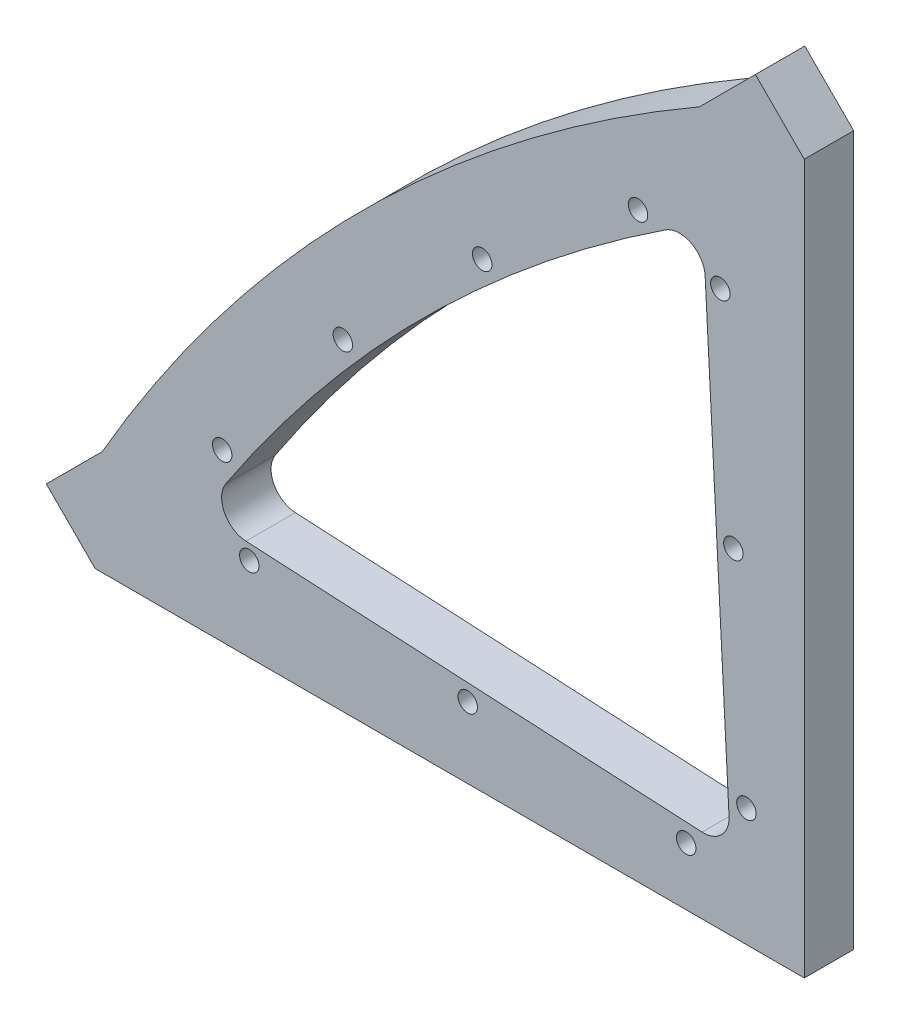
SolidWorks part; units mm, degrees
ref_plane "Front Plane" through (0, 0, 0) normal (0, 0, 1) x (1, 0, 0)
ref_plane "Top Plane" through (0, 0, 0) normal (0, 1, 0) x (1, 0, 0)
ref_plane "Right Plane" through (0, 0, 0) normal (1, 0, 0) x (0, 0, -1)
sketch "Sketch1" plane through (0, 0, 0) normal (0, 0, 1) x (1, 0, 0)
  line L2 (-60.2624, -86.0896) -> (122.0368, -86.0896)
  line L6 (-42.1742, -86.4706) -> (122.4178, -86.4706) construction
  line L7 (117.3378, -81.3906) -> (130.0378, -94.0906) construction
  line L8 (122.0368, 96.2096) -> (122.0368, -86.0896)
  line L9 (-72.8348, -73.5173) -> (-60.2624, -86.0896)
  line L10 (122.0368, -86.0896) -> (-41.4122, 77.3594) construction
  line L15 (-194.9829, 48.6309) -> (-70.337, -76.0151) construction
  line L31 (-71.7047, -74.6473) -> (-63.733, -82.6191) construction
  line L32 (-58.4664, -59.1489) -> (-72.8348, -73.5173)
  line L33 (95.096, 94.4135) -> (109.4644, 108.7819)
  line L34 (109.4644, 108.7819) -> (122.0368, 96.2096)
  arc A2 (95.096, 94.4135) -> (-58.4664, -59.1489) centre (304.2547, -268.3076) ccw
  arc A3 (86.8507, 75.0529) -> (-39.1057, -50.9035) centre (304.2547, -268.3076) ccw construction
  dimension "D1" = 17.78
  dimension "D2" = 0.381
  dimension "D3" = 20.32
extrude "Boss-Extrude1" add sketch "Sketch1" along normal blind 12.7
sketch "Sketch2" plane through (0, 0, 12.7) normal (0, 0, 1) x (1, 0, 0)
  line L0 (106.3271, 64.9875) -> (112.928, -60.9641) construction
  line L1 (96.9113, -76.9808) -> (-29.0404, -70.38) construction
  line L2 (96.5484, 57.4472) -> (102.6933, -59.8056)
  line L4 (95.7527, -66.7462) -> (-21.5001, -60.6012)
  line L5 (96.1811, 64.4558) -> (102.7819, -61.4958) construction
  line L6 (97.443, -66.8347) -> (-28.5086, -60.2339) construction
  arc A0 (112.928, -60.9641) -> (96.9113, -76.9808) centre (97.7089, -61.7617) cw construction
  arc A1 (96.9113, -76.9808) -> (112.928, -60.9641) centre (97.7089, -61.7617) ccw construction
  arc A2 (-29.0404, -70.38) -> (-39.1057, -50.9035) centre (-28.3757, -57.6974) cw construction
  arc A3 (-39.1057, -50.9035) -> (86.8507, 75.0529) centre (304.2547, -268.3076) cw construction
  arc A4 (86.8507, 75.0529) -> (106.3271, 64.9875) centre (93.6445, 64.3229) cw construction
  arc A5 (-26.6699, -50.374) -> (86.3212, 62.617) centre (304.2547, -268.3076) cw
  arc A12 (-30.5217, -56.3386) -> (92.2858, 66.4689) centre (304.2547, -268.3076) cw construction
  arc A13 (86.3212, 62.617) -> (96.5484, 57.4472) centre (89.9534, 57.1016) cw
  arc A24 (-21.5001, -60.6012) -> (-26.6699, -50.374) centre (-21.1544, -54.0062) cw
  arc A25 (95.7527, -66.7462) -> (102.6933, -59.8056) centre (96.0984, -60.1512) ccw
  arc A35 (92.2858, 66.4689) -> (96.1811, 64.4558) centre (93.6445, 64.3229) cw construction
  arc A36 (-28.5086, -60.2339) -> (-30.5217, -56.3386) centre (-28.3757, -57.6974) cw construction
  arc A37 (102.7819, -61.4958) -> (97.443, -66.8347) centre (97.7089, -61.7617) cw construction
  dimension "D2" = 6.604
  dimension "D1" = 10.16
extrude "Cut-Extrude1" cut sketch "Sketch2" against normal through all
sketch "Sketch3" plane through (0, 0, 0) normal (0, 0, -1) x (-1, 0, 0)
  circle A0 centre (-100.4496, 56.5997) radius 2.5
  circle A1 centre (-79.2876, 63.5687) radius 2.5
  circle A2 centre (-39.2281, 32.5461) radius 2.5
  circle A3 centre (-3.401, -3.281) radius 2.5
  circle A4 centre (27.6215, -43.3404) radius 2.5
  circle A5 centre (20.6525, -64.5024) radius 2.5
  circle A6 centre (-35.5084, -67.8561) radius 2.5
  circle A7 centre (-91.6694, -71.2098) radius 2.5
  circle A8 centre (-107.157, -55.7222) radius 2.5
  circle A9 centre (-103.8033, 0.4387) radius 2.5
  dimension "D1" = 5
extrude "Cut-Extrude2" cut sketch "Sketch3" against normal through all
